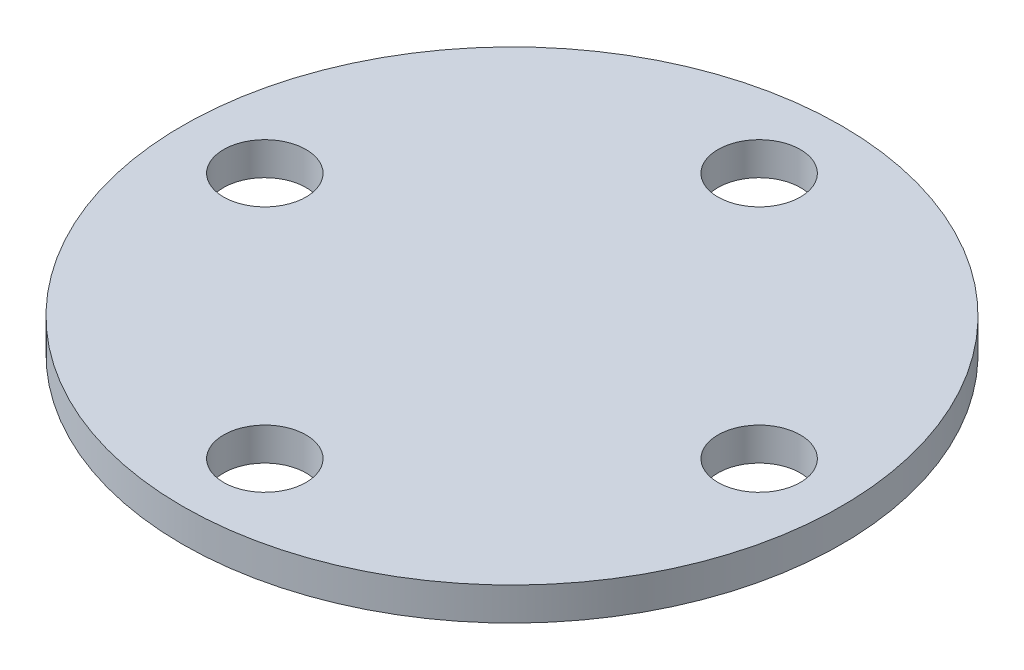
SolidWorks part; units mm, degrees
ref_plane "Front Plane" through (0, 0, 0) normal (0, 0, 1) x (1, 0, 0)
ref_plane "Top Plane" through (0, 0, 0) normal (0, 1, 0) x (1, 0, 0)
ref_plane "Right Plane" through (0, 0, 0) normal (1, 0, 0) x (0, 0, -1)
sketch "Sketch1" plane through (0, 0, 0) normal (0, 1, 0) x (1, 0, 0)
  line L0 (0, 0) -> (0, 25.4) construction
  circle A0 centre (0, 0) radius 25.4
  circle A1 centre (0, 19.05) radius 3.175
  circle A2 centre (19.05, 0) radius 3.175
  circle A3 centre (0, -19.05) radius 3.175
  circle A4 centre (-19.05, 0) radius 3.175
  point P14 (0, 0)
  dimension "D1" = 50.8
  dimension "D2" = 6.35
  dimension "D3" = 19.05
  dimension "D4" = 4
extrude "Boss-Extrude1" add sketch "Sketch1" along normal blind 2.54
